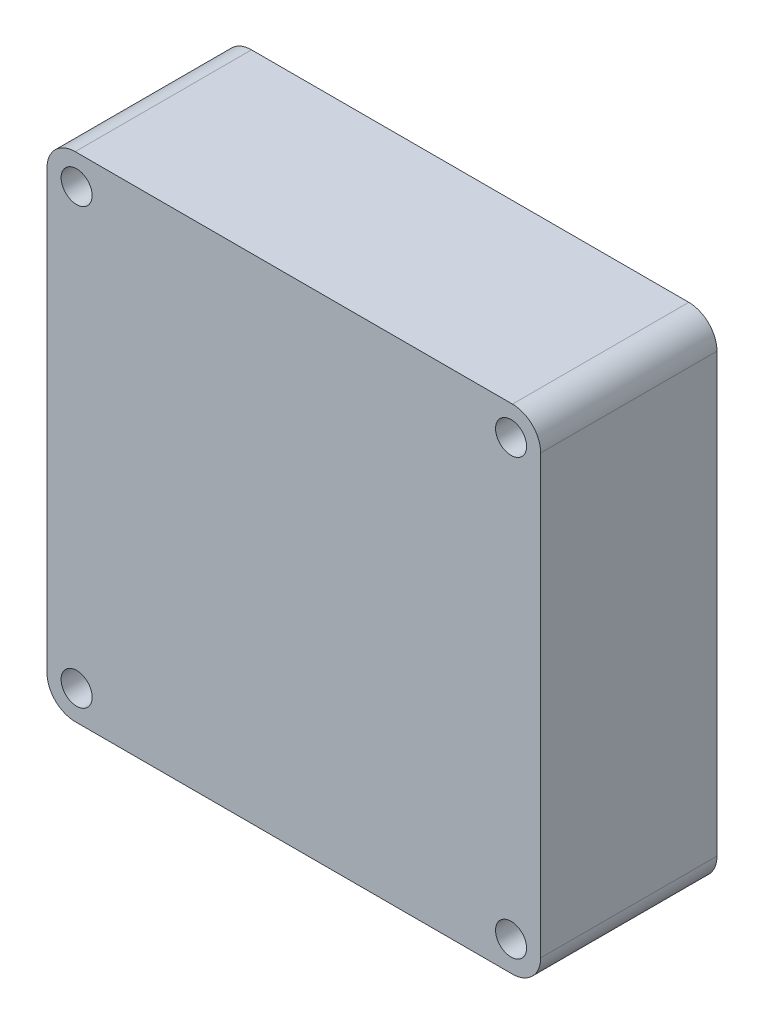
SolidWorks part; units mm, degrees
ref_plane "Front Plane" through (0, 0, 0) normal (0, 0, 1) x (1, 0, 0)
ref_plane "Top Plane" through (0, 0, 0) normal (0, 1, 0) x (1, 0, 0)
ref_plane "Right Plane" through (0, 0, 0) normal (1, 0, 0) x (0, 0, -1)
sketch "Sketch1" plane through (0, 0, 0) normal (0, 0, 1) x (1, 0, 0)
  line L1 (-35, -35) -> (35, -35)
  line L2 (-35, -35) -> (-35, 35)
  line L3 (-35, 35) -> (35, 35)
  line L4 (35, -35) -> (35, 35)
  line L5 (-35, -35) -> (35, 35) construction
  line L6 (-35, 35) -> (35, -35) construction
  point P0 (0, 0)
  dimension "D1" = 70
extrude "Boss-Extrude1" add sketch "Sketch1" along normal blind 25
sketch "Sketch2" plane through (0, 0, 25) normal (0, 0, 1) x (1, 0, 0)
  line L4 (35, -35) -> (35, 35)
  line L5 (35, 35) -> (-35, 35)
  line L6 (-35, 35) -> (-35, -35)
  line L7 (-35, -35) -> (35, -35)
  line L8 (35, -35) -> (35, 35) construction
  line L9 (35, 35) -> (-35, 35) construction
  line L10 (-35, 35) -> (-35, -35) construction
  line L11 (-35, -35) -> (35, -35) construction
  line L13 (-30.8, -30.8) -> (30.8, -30.8) construction
  line L14 (-30.8, -30.8) -> (-30.8, 30.8) construction
  line L15 (-30.8, 30.8) -> (30.8, 30.8) construction
  line L16 (30.8, -30.8) -> (30.8, 30.8) construction
  line L17 (-30.8, -30.8) -> (30.8, 30.8) construction
  line L18 (-30.8, 30.8) -> (30.8, -30.8) construction
  circle A0 centre (-30.8, 30.8) radius 2.2
  circle A1 centre (30.8, 30.8) radius 2.2
  circle A2 centre (30.8, -30.8) radius 2.2
  circle A3 centre (-30.8, -30.8) radius 2.2
  point P6 (0, 0)
  point P13 (-33, 30.8)
  point P14 (33, 30.8)
  dimension "D2" = 4.4
  dimension "D3" = 66
  dimension "D1" = 0
extrude "Cut-Extrude1" cut sketch "Sketch2" against normal through all contours A3
fillet "Fillet1" radius 4 4 edges at (35, -35, 12.5) (35, 35, 12.5) (-35, -35, 12.5) (-35, 35, 12.5)
